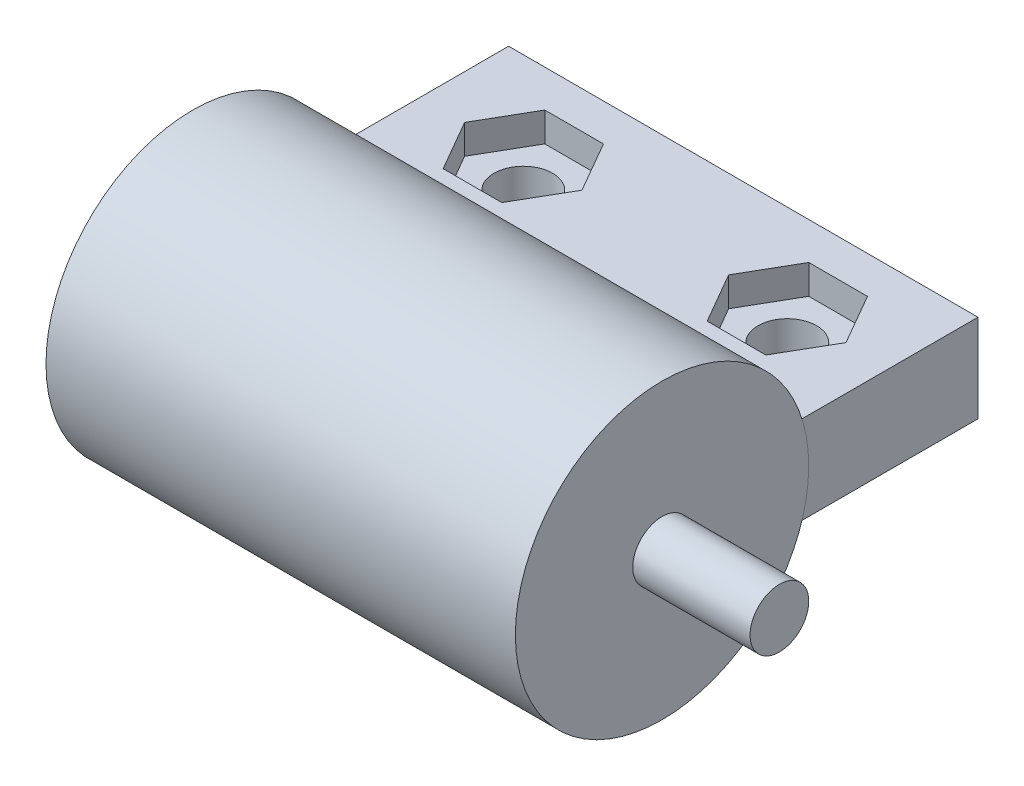
SolidWorks part; units mm, degrees
ref_plane "前视基准面" through (0, 0, 0) normal (0, 0, 1) x (1, 0, 0)
ref_plane "上视基准面" through (0, 0, 0) normal (0, 1, 0) x (1, 0, 0)
ref_plane "右视基准面" through (0, 0, 0) normal (1, 0, 0) x (0, 0, -1)
other "Configuration Table"
sketch "草图1" plane through (0, 0, 0) normal (0, 1, 0) x (1, 0, 0)
  line L0 (0, 1.5) -> (8, 1.5) construction
  line L1 (0, 0) -> (8, 0)
  line L2 (0, 0) -> (0, 3)
  line L3 (0, 3) -> (8, 3)
  line L4 (8, 0) -> (8, 3)
  circle A0 centre (1.75, 1.5) radius 0.5
  circle A1 centre (6.25, 1.5) radius 0.5
  dimension "D3" = 1
  dimension "D4" = 1
  dimension "D1" = 8
  dimension "D2" = 3
  dimension "D5" = 1.75
  dimension "D6" = 1.75
extrude "凸台-拉伸1" add sketch "草图1" along normal blind 1
sketch "草图2" plane through (0, 1, 0) normal (0, 1, 0) x (1, 0, 0)
  line L0 (4, 3) -> (4, 0) construction
  line L1 (8, 3) -> (0, 3) construction
  line L2 (0, 0) -> (8, 0) construction
  line L3 (0, 1.5) -> (4, 1.5) construction
  line L4 (0, 3) -> (0, 0) construction
  line L5 (0, 3) -> (4, 3)
  line L6 (1.75, 3) -> (1.75, 0) construction
  line L7 (2.25, 2.366) -> (1.25, 2.366)
  line L8 (2.25, 2.366) -> (2.75, 1.5)
  line L9 (1.25, 2.366) -> (0.75, 1.5)
  line L10 (2.25, 0.634) -> (2.75, 1.5)
  line L11 (2.25, 0.634) -> (1.25, 0.634)
  line L12 (1.25, 0.634) -> (0.75, 1.5)
  line L13 (5.75, 2.366) -> (5.25, 1.5)
  line L14 (5.75, 0.634) -> (5.25, 1.5)
  line L15 (5.75, 0.634) -> (6.75, 0.634)
  line L16 (6.75, 0.634) -> (7.25, 1.5)
  line L17 (6.75, 2.366) -> (7.25, 1.5)
  line L18 (5.75, 2.366) -> (6.75, 2.366)
  line L19 (1.75, 2) -> (1.75, 1) construction
  circle A1 centre (1.75, 1.5) radius 0.5 construction
  point P19 (1.75, 2.366)
  line M10 (0, 3) -> (0, 0)
  line M11 (0, 0) -> (8, 0)
  line M12 (8, 0) -> (8, 3)
  line M13 (8, 3) -> (0, 3)
  dimension "D1" = 60
  dimension "D2" = 0.5
  dimension "D3" = 1
extrude "凸台-拉伸2" add sketch "草图2" along normal blind 0.5 contours L11 L12 L9 L7 L8 L10 L13 L18 L17 L16 L15 L14 M13 M10 M11 M12
sketch "草图3" plane through (8, 0, 0) normal (1, 0, 0) x (0, 0, -1)
  line L0 (5, 0.75) -> (0, 0.75) construction
  line L6 (3, 1.5) -> (3, 0)
  circle A0 centre (-2.3848, 0.75) radius 2.5
  point P8 (3, 0.75)
  dimension "D1" = 5
extrude "凸台-拉伸3" add sketch "草图3" against normal up to surface (8 mm away) separate body contours A0 up to face at (0, 0.75, -1.5)
sketch "草图5" plane through (0, 0, 0) normal (-1, 0, 0) x (0, 0, 1)
  circle A0 centre (2.3848, 0.75) radius 0.5
  dimension "D1" = 1
sketch "草图6" plane through (8, 0, 0) normal (1, 0, 0) x (0, 0, -1)
  circle A0 centre (-2.3848, 0.75) radius 0.5
  dimension "D1" = 1
extrude "凸台-拉伸4" add sketch "草图6" along normal blind 2 contours A0
